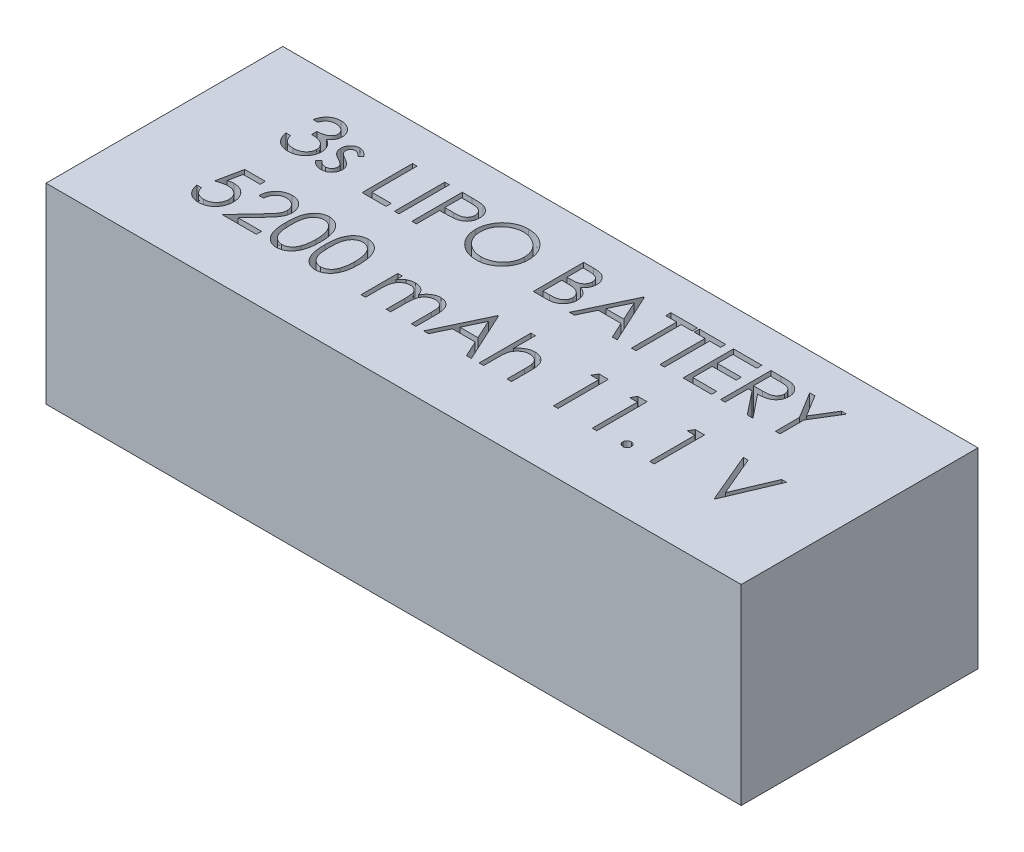
SolidWorks part; units mm, degrees
ref_plane "Front Plane" through (0, 0, 0) normal (0, 0, 1) x (1, 0, 0)
ref_plane "Top Plane" through (0, 0, 0) normal (0, 1, 0) x (1, 0, 0)
ref_plane "Right Plane" through (0, 0, 0) normal (1, 0, 0) x (0, 0, -1)
sketch "Sketch1" plane through (0, 0, 0) normal (0, 1, 0) x (1, 0, 0)
  line L1 (0, 0) -> (138, 0)
  line L2 (0, 0) -> (0, 47)
  line L3 (0, 47) -> (138, 47)
  line L4 (138, 0) -> (138, 47)
  dimension "D1" = 138
  dimension "D2" = 47
extrude "Boss-Extrude1" add sketch "Sketch1" along normal blind 38
sketch "Sketch2" plane through (0, 38, 0) normal (0, 1, 0) x (1, 0, 0)
  text T0 "3s LIPO BATTERY\r\n5200 mAh 11.1 V" font "Century Gothic" height 10
  point P1 (31.5508, 16.5968)
  point P2 (40.8717, 24.7393)
  point P3 (50.7733, 61.6791)
  point P4 (46.2091, 65.7266)
extrude "Cut-Extrude1" cut sketch "Sketch2" against normal blind 10
